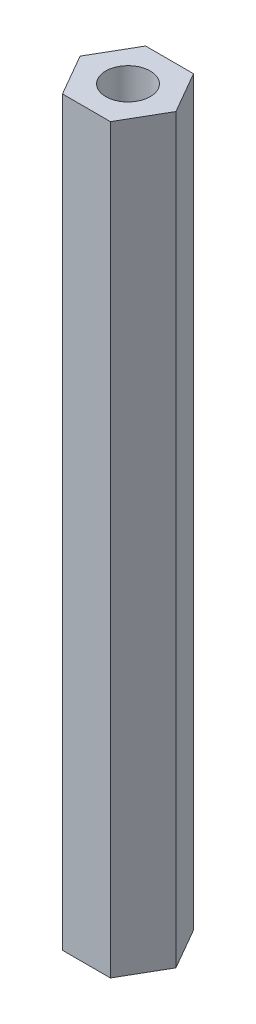
SolidWorks part; units mm, degrees
material "尼龙 101"
ref_plane "前视基准面" through (0, 0, 0) normal (0, 0, 1) x (1, 0, 0)
ref_plane "上视基准面" through (0, 0, 0) normal (0, 1, 0) x (1, 0, 0)
ref_plane "右视基准面" through (0, 0, 0) normal (1, 0, 0) x (0, 0, -1)
sketch "草图1" plane through (0, 0, 0) normal (0, 1, 0) x (1, 0, 0)
  line L1 (1.6182, 2.7991) -> (-1.615, 2.8009)
  line L2 (-1.615, 2.8009) -> (-3.2332, 0.0019)
  line L3 (-3.2332, 0.0019) -> (-1.6182, -2.7991)
  line L4 (-1.6182, -2.7991) -> (1.615, -2.8009)
  line L5 (1.615, -2.8009) -> (3.2332, -0.0019)
  line L6 (3.2332, -0.0019) -> (1.6182, 2.7991)
  circle A0 centre (0, 0) radius 2.8 construction
  circle A1 centre (0, 0) radius 1.5
  dimension "D2" = 3
  dimension "D1" = 5.6
extrude "凸台-拉伸1" add sketch "草图1" along normal blind 50
